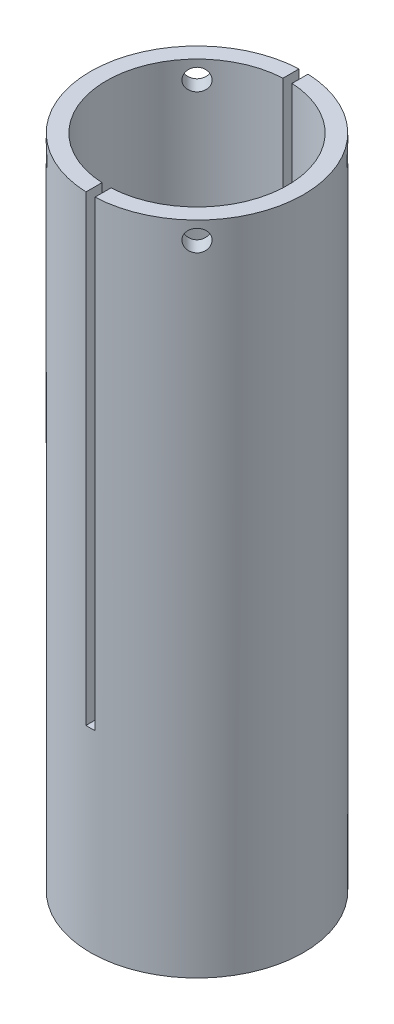
SolidWorks part; units mm, degrees
material "Brass"
ref_plane "Front Plane" through (0, 0, 0) normal (0, 0, 1) x (1, 0, 0)
ref_plane "Top Plane" through (0, 0, 0) normal (0, 1, 0) x (1, 0, 0)
ref_plane "Right Plane" through (0, 0, 0) normal (1, 0, 0) x (0, 0, -1)
sketch "Sketch1" plane through (0, 0, 0) normal (0, 1, 0) x (1, 0, 0)
  circle A0 centre (0, 0) radius 3
  circle A1 centre (0, 0) radius 2.55
  dimension "D1" = 6
  dimension "D2" = 0.45
extrude "Boss-Extrude1" add sketch "Sketch1" along normal blind 18.47
sketch "Sketch2" plane through (0, 0, 0) normal (0, 0, 1) x (1, 0, 0)
  line L0 (2.55, 18.47) -> (-2.55, 18.47) construction
  line L1 (-0.127, 18.47) -> (0.127, 18.47)
  line L2 (-0.127, 18.47) -> (-0.127, 5.47)
  line L3 (-0.127, 5.47) -> (0.127, 5.47)
  line L4 (0.127, 18.47) -> (0.127, 5.47)
  line L5 (-0.127, 18.47) -> (0.127, 5.47) construction
  line L6 (-0.127, 5.47) -> (0.127, 18.47) construction
  point P0 (0, 11.97)
  dimension "D1" = 13
  dimension "D2" = 0.254
extrude "Cut-Extrude1" cut sketch "Sketch2" against normal through all and the other way through all
hole_wizard "Ø0.6 (0.6) Diameter Hole1" positions "3DSketch1" profile "Sketch3" hole size "Ø0.6" standard "ANSI Metric" end condition up to next
sketch3d "3DSketch1"
  line L0 (0, 18.47, 0) -> (0, 17.97, 0) construction
  line L1 (0, 17.97, 0) -> (2.1213, 17.97, -2.1213) construction
  line L4 (0, 17.97, 0) -> (2.1213, 17.97, 2.1213) construction
  line L5 (2.1213, 17.97, 2.1213) -> (2.1213, 17.97, -2.1213) construction
  line L6 (0, 17.97, 0) -> (-2.1213, 17.97, 2.1213) construction
  line L9 (0, 17.97, 0) -> (-2.1213, 17.97, -2.1213) construction
  arc A0 (-0.127, 18.47, -2.9973) -> (-0.127, 18.47, 2.9973) centre (0, 18.47, 0) ccw construction
  point P15 (0, 21.47, 0)
  point P16 (2.1213, 17.97, 2.1213)
  point P18 (2.1213, 17.97, -2.1213)
  point P29 (-2.1213, 17.97, 2.1213)
  point P31 (-2.1213, 17.97, -2.1213)
  dimension "D1" = 0.5
sketch "Sketch3" plane through (2.1213, 17.97, 2.1213) normal (0, 1, 0) x (0.7071, 0, -0.7071)
  line L0 (0, 0) -> (0, 0.45)
  line L1 (0, 0.45) -> (0.3, 0.45)
  line L2 (0.3, 0.45) -> (0.3, 0)
  line L5 (0.3, 0) -> (0, 0)
  line L11 (0, -6.35) -> (0, 107.95) construction
  dimension "Thru Hole Dia." = 0.6
  dimension "Thru Hole Depth" = 0.45
